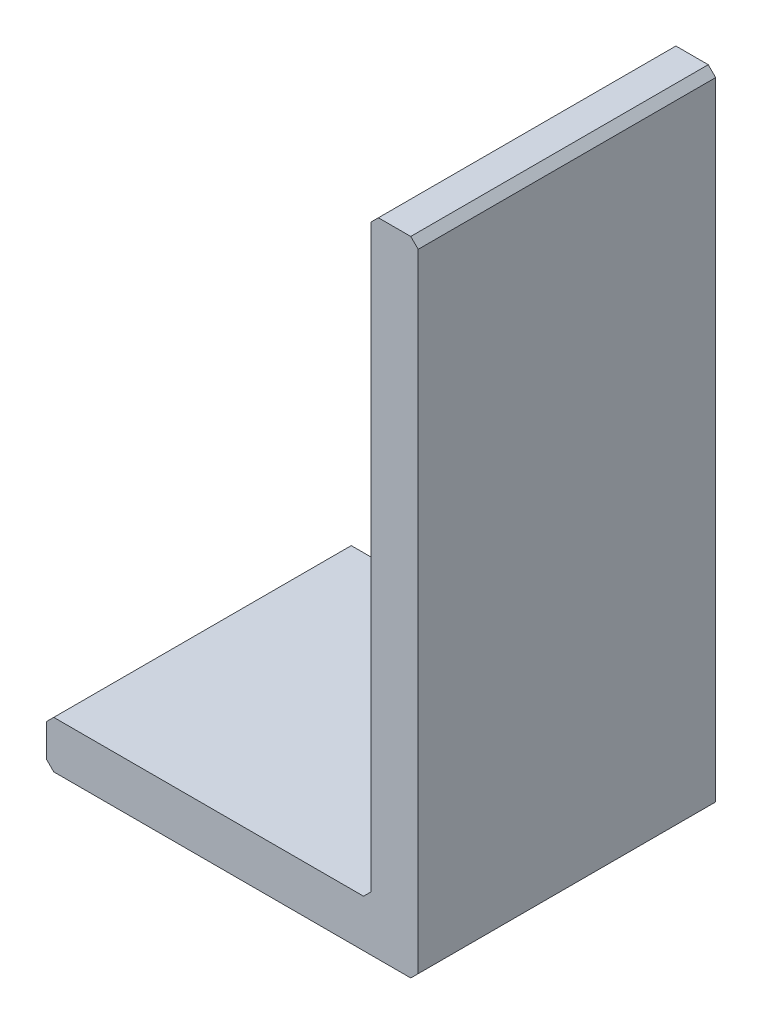
SolidWorks part; units mm, degrees
ref_plane "Front Plane" through (0, 0, 0) normal (0, 0, 1) x (1, 0, 0)
ref_plane "Top Plane" through (0, 0, 0) normal (0, 1, 0) x (1, 0, 0)
ref_plane "Right Plane" through (0, 0, 0) normal (1, 0, 0) x (0, 0, -1)
sketch "Sketch1" plane through (0, 0, 0) normal (0, 1, 0) x (1, 0, 0)
  line L1 (-12.5, -10) -> (12.5, -10)
  line L2 (-12.5, -10) -> (-12.5, 10)
  line L3 (-12.5, 10) -> (12.5, 10)
  line L4 (12.5, -10) -> (12.5, 10)
  line L5 (-12.5, -10) -> (12.5, 10) construction
  line L6 (-12.5, 10) -> (12.5, -10) construction
  point P0 (0, 0)
  dimension "D1" = 20
  dimension "D2" = 25
extrude "Boss-Extrude1" add sketch "Sketch1" along normal blind 3.175
sketch "Sketch3" plane through (0, 3.175, 0) normal (0, 1, 0) x (1, 0, 0)
  line L0 (-12.5, -10) -> (12.5, -10) construction
  line L1 (12.5, 10) -> (9.325, 10)
  line L2 (12.5, 10) -> (12.5, -10)
  line L3 (12.5, -10) -> (9.325, -10)
  line L4 (9.325, 10) -> (9.325, -10)
  dimension "D1" = 3.175
extrude "Boss-Extrude2" add sketch "Sketch3" along normal blind 40
chamfer "Chamfer1" distance 0.5 angle 45 6 edges at (-12.5, 0, 0) (-12.5, 3.175, 0) (12.5, 43.175, 0) (9.325, 43.175, 0) (12.5, 0, 0) (9.325, 3.175, 0)
